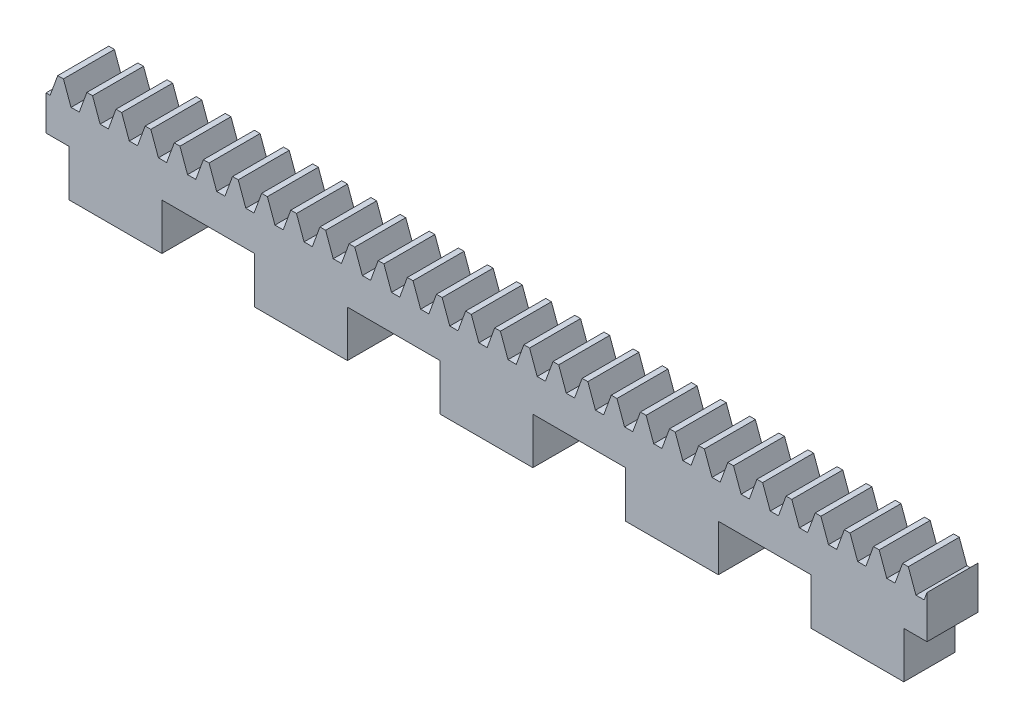
SolidWorks part; units mm, degrees
extrude "Blank" add sketch "BlankSke" against normal blind 5.5
sketch "BlankSke" plane through (0, 0, 0) normal (0, 0, 1) x (1, 0, 0)
  line L1 (0, 0) -> (95, 0)
  line L2 (0, 0) -> (0, 11)
  line L3 (0, 11) -> (95, 11)
  line L4 (95, 0) -> (95, 11)
  dimension "Length" = 95
  dimension "Blank_height" = 11
ref_plane "Plane1" through (0, 0, 0) normal (0, 0, 1) x (1, 0, 0)
ref_plane "Plane2" through (0, 0, 0) normal (0, 1, 0) x (1, 0, 0)
ref_plane "Plane3" through (0, 0, 0) normal (1, 0, 0) x (0, 0, -1)
sketch "HoldingSke" plane through (0, 0, 0) normal (0, 1, 0) x (1, 0, 0)
  line L0 (0, 0) -> (0.1392, 0.9903)
  line L1 (-15, 0) -> (100, 0) construction
  line L2 (0, 0) -> (-2.1039, 2.3779)
  line L3 (0, 0) -> (-11.863, 4.5341)
  line L4 (0, 0) -> (7.3238, 4.5764)
  line L5 (0, 0) -> (-23.7986, -8.8762)
  line L6 (0, 0) -> (-10.5278, -7.1032)
  line L9 (-71.009, 38.7566) -> (18.2618, 71.2485)
  line L10 (-76.2, 3.3779) -> (-66.2, 3.3779)
  line L11 (0, 0) -> (-5.5, 0)
  line L12 (-76.2, 101.6) -> (-76.162, 101.6)
  line L13 (24.9733, 27.94) -> (52.9518, 28.4284)
  line L14 (24.9733, 27.94) -> (24.9743, 27.94)
  line L15 (24.9733, 27.94) -> (100.4006, 29.5858)
  circle A0 centre (0, 0) radius 19.05
  circle A1 centre (0, 0) radius 5
  circle A2 centre (0, 0) radius 12.7
  dimension "MPH" = 10
  dimension "Diameter" = 38.1
  dimension "Num_teeth" = 32
  dimension "Pitch" = 1
  dimension "Show_teeth" = 998
  dimension "Thickness" = 12.7
  dimension "Ap" = 20
  dimension "Pitch_height" = 10
  dimension "Width" = 5.5
  dimension "Backlash" = 0.038
  dimension "Addendum_fac" = 1
  dimension "Dedendum_fac" = 1.25
  dimension "Clearance_fac" = 0.25
  dimension "Dedendum_add" = 0.001
  dimension "Length" = 95
  dimension "Module" = 1
sketch "TooCutSkeIll" plane through (0, 0, 0) normal (0, 0, 1) x (1, 0, 0)
  line L0 (-1.2538, 10.9737) -> (-0.5045, 8.9152)
  line L1 (-0.2687, 8.75) -> (0.2687, 8.75)
  line L2 (0.5045, 8.9152) -> (1.2538, 10.9737)
  line L3 (95, 11) -> (0, 11) construction
  line L4 (0, 0) -> (0, 64.897) construction
  line L5 (-13.208, 10) -> (12.954, 10) construction
  line L6 (0, 0) -> (95, 0) construction
  line L7 (0.8994, 10) -> (0.8994, 48.7463) construction
  line L8 (-0.8994, 10) -> (-0.8994, 48.7463) construction
  line L9 (1.2914, 11) -> (1.2914, 11.0254)
  line L10 (-1.2914, 11) -> (-1.2914, 11.0254)
  line L11 (-1.2914, 11.0254) -> (1.2914, 11.0254)
  arc A0 (0.2687, 8.75) -> (0.5045, 8.9152) centre (0.2687, 9.001) ccw
  arc A1 (-0.5045, 8.9152) -> (-0.2687, 8.75) centre (-0.2687, 9.001) ccw
  arc A2 (1.2914, 11) -> (1.2538, 10.9737) centre (1.2914, 10.96) ccw
  arc A3 (-1.2538, 10.9737) -> (-1.2914, 11) centre (-1.2914, 10.96) ccw
  dimension "Pitch_height" = 10
  dimension "Addendum_plus" = 1.0254
  dimension "Pressure_angle" = 20
  dimension "Gap_width" = 1.7988
  dimension "Dedendum" = 1.25
extrude "ToothCutIll" [suppressed] cut sketch "TooCutSkeIll" against normal through all
sketch "TooCutSkeSim" plane through (0, 0, 0) normal (0, 0, 1) x (1, 0, 0)
  line L0 (0.4444, 8.75) -> (-0.4444, 8.75)
  line L1 (1.2726, 11.0254) -> (0.4444, 8.75)
  line L2 (0, 17.4625) -> (0, 53.467) construction
  line L3 (1.2726, 11.0254) -> (-1.2726, 11.0254)
  line L6 (-1.2726, 11.0254) -> (-0.4444, 8.75)
  line L9 (-0.8994, 10) -> (0.8994, 10) construction
  line L10 (0, 0) -> (95, 0) construction
  line L11 (0.8994, 10) -> (0.8994, 53.467) construction
  line L12 (-0.8994, 10) -> (-0.8994, 53.467) construction
  dimension "Pitch_height" = 10
  dimension "Addendum_plus" = 1.0254
  dimension "Pressure_angle" = 20
  dimension "Gap_width" = 1.7988
  dimension "Dedendum" = 1.25
extrude "ToothCutSim" cut sketch "TooCutSkeSim" against normal through all
pattern_linear "TeethCuts" count 31 spacing 3.1416 along (1, 0, 0) of "ToothCutIll", "ToothCutSim"
sketch "ｽｹｯﾁ1" plane through (0, 0, 0) normal (0, 0, 1) x (1, 0, 0)
  line L0 (0, 8.75) -> (0, 0) construction
  line L1 (-7.5, 0) -> (2.5, 0)
  line L2 (-7.5, 0) -> (-7.5, 5)
  line L3 (-7.5, 5) -> (2.5, 5)
  line L4 (2.5, 0) -> (2.5, 5)
  line L5 (0, 0) -> (95, 0) construction
  line L6 (12.5, 0) -> (12.5, 5)
  line L7 (12.5, 0) -> (22.5, 0)
  line L8 (22.5, 0) -> (22.5, 5)
  line L9 (12.5, 5) -> (22.5, 5)
  line L10 (32.5, 0) -> (32.5, 5)
  line L11 (32.5, 0) -> (42.5, 0)
  line L12 (42.5, 0) -> (42.5, 5)
  line L13 (32.5, 5) -> (42.5, 5)
  line L14 (52.5, 0) -> (52.5, 5)
  line L15 (52.5, 0) -> (62.5, 0)
  line L16 (62.5, 0) -> (62.5, 5)
  line L17 (52.5, 5) -> (62.5, 5)
  line L18 (72.5, 0) -> (72.5, 5)
  line L19 (72.5, 0) -> (82.5, 0)
  line L20 (82.5, 0) -> (82.5, 5)
  line L21 (72.5, 5) -> (82.5, 5)
  line L22 (92.5, 0) -> (92.5, 5)
  line L23 (92.5, 0) -> (102.5, 0)
  line L24 (102.5, 0) -> (102.5, 5)
  line L25 (92.5, 5) -> (102.5, 5)
  dimension "D1" = 10
  dimension "D2" = 5
  dimension "D3" = 2.5
  dimension "D4" = 6
extrude "ｶｯﾄ - 押し出し1" cut sketch "ｽｹｯﾁ1" against normal through all
equation "' \"Module@HoldingSke\" = 6.35"
equation "' \"Num_teeth@HoldingSke\" = 12"
equation "' \"Ap@HoldingSke\" =  20"
equation "' \"Ap@HoldingSke\" = 20"
equation "' \"Width@HoldingSke\" = 0.25 * 25.4"
equation "' \"Show_teeth@HoldingSke\" = 500"
equation "' \"Backlash@HoldingSke\" = 0.009 * 25.4"
equation "' \"Addendum_fac@HoldingSke\" = 1.0"
equation "' \"Dedendum_fac@HoldingSke\" = 1.25"
equation "' \"Dedendum_add@HoldingSke\" = 0.00005 * 25.4"
equation "' \"Clearance_fac@HoldingSke\" = 0.25"
equation "' \"Pitch_height@HoldingSke\" = 1 * 25.4"
equation "' \"Length@HoldingSke\" = 4.71 * 25.4"
equation "\"Pitch@HoldingSke\" = 1 / \"Module@HoldingSke\""
equation "\"MPH@HoldingSke\" = \"Dedendum_fac@HoldingSke\" / \"Pitch@HoldingSke\" + 2 * \"Dedendum_add@HoldingSke\" + 0.002 * 25.4"
equation "\"MPH@HoldingSke\" = ((sgn( \"MPH@HoldingSke\" - \"Pitch_height@HoldingSke\")+1)*( \"MPH@HoldingSke\" - \"Pitch_height@HoldingSke\"))/2 + \"Pitch_height@HoldingSke\""
equation "\"Blank_height@BlankSke\" = \"Pitch_height@HoldingSke\" + \"Addendum_fac@HoldingSke\"  / \"Pitch@HoldingSke\" "
equation "\"Length@BlankSke\" =  \"Length@HoldingSke\""
equation "\"Face_width@Blank\" = \"Width@HoldingSke\""
equation "\"Pressure_angle@TooCutSkeIll\" = \"Ap@HoldingSke\""
equation "\"Addendum_plus@TooCutSkeIll\" =  \"Addendum_fac@HoldingSke\"  / \"Pitch@HoldingSke\" + 0.001 *25.4"
equation "\"Dedendum@TooCutSkeIll\" = \"Dedendum_fac@HoldingSke\"  / \"Pitch@HoldingSke\""
equation "\"Pitch_height@TooCutSkeIll\" =  \"MPH@HoldingSke\""
equation "\"Gap_width@TooCutSkeIll\" = 3.14159265 / 2 / \"Pitch@HoldingSke\" + 6 * \"Backlash@HoldingSke\""
equation "\"Pressure_angle@TooCutSkeSim\" = \"Ap@HoldingSke\""
equation "\"Addendum_plus@TooCutSkeSim\" =  \"Addendum_fac@HoldingSke\"  / \"Pitch@HoldingSke\" + 0.001 * 25.4"
equation "\"Dedendum@TooCutSkeSim\" = \"Dedendum_fac@HoldingSke\"  / \"Pitch@HoldingSke\""
equation "\"Pitch_height@TooCutSkeSim\" =  \"MPH@HoldingSke\""
equation "\"Gap_width@TooCutSkeSim\" = 3.14159265 / 2 / \"Pitch@HoldingSke\" + 6 * \"Backlash@HoldingSke\""
equation "\"Root_fillet@TooCutSkeIll\" = \"Clearance_fac@HoldingSke\" / \"Pitch@HoldingSke\" + \"Dedendum_add@HoldingSke\""
equation "\"Break_rad@TooCutSkeIll\" = 0.02 / \"Pitch@HoldingSke\" * 2"
equation "\"Linear_pitch@TeethCuts\" = 3.14159265 / \"Pitch@HoldingSke\""
equation "\"Num_teeth@HoldingSke\" = int( ( \"Length@HoldingSke\" + 0 ) / (3.14159265 / \"Pitch@HoldingSke\")) + 0.9999  + 1"
equation " \"Num_teeth@TeethCuts\" = int( \"Show_teeth@HoldingSke\" ) + 1"
equation " \"Num_teeth@TeethCuts\" = ((sgn( \"Num_teeth@TeethCuts\" - \"Num_teeth@HoldingSke\" )-1)*( \"Num_teeth@TeethCuts\" - \"Num_teeth@HoldingSke\" ))/-2+ \"Num_teeth@HoldingSke\""
equation " \"Num_teeth@TeethCuts\" = ((sgn( \"Num_teeth@TeethCuts\" - 2.0)+1)*( \"Num_teeth@TeethCuts\" - 2.0))/2 +2.0"
